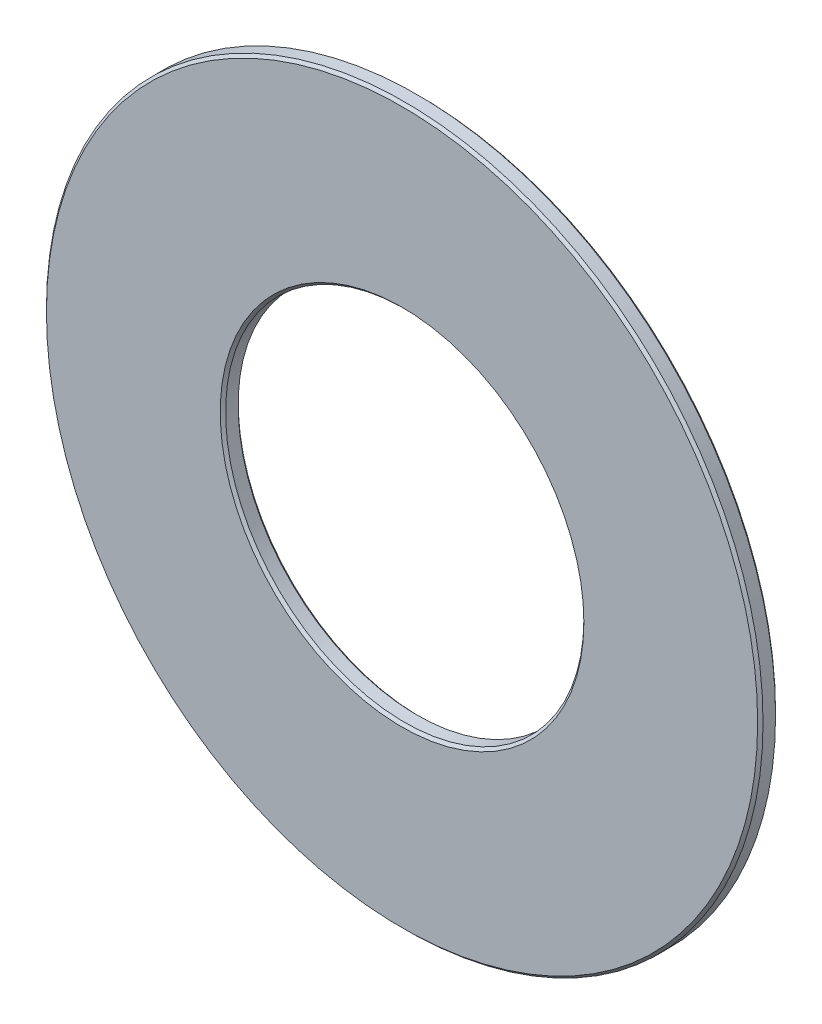
SolidWorks part; units mm, degrees
ref_plane "前视基准面" through (0, 0, 0) normal (0, 0, 1) x (1, 0, 0)
ref_plane "上视基准面" through (0, 0, 0) normal (0, 1, 0) x (1, 0, 0)
ref_plane "右视基准面" through (0, 0, 0) normal (1, 0, 0) x (0, 0, -1)
sketch "草图1" plane through (0, 0, 0) normal (0, 0, 1) x (1, 0, 0)
  circle A0 centre (0, 0) radius 2
  circle A1 centre (0, 0) radius 4
  dimension "D1" = 4
  dimension "D2" = 8
extrude "凸台-拉伸1" add sketch "草图1" along normal mid plane 0.2
chamfer "倒角1" distance 0.03 angle 45 4 edges at (2, 0, 0.1) (2, 0, -0.1) (4, 0, -0.1) (4, 0, 0.1)
